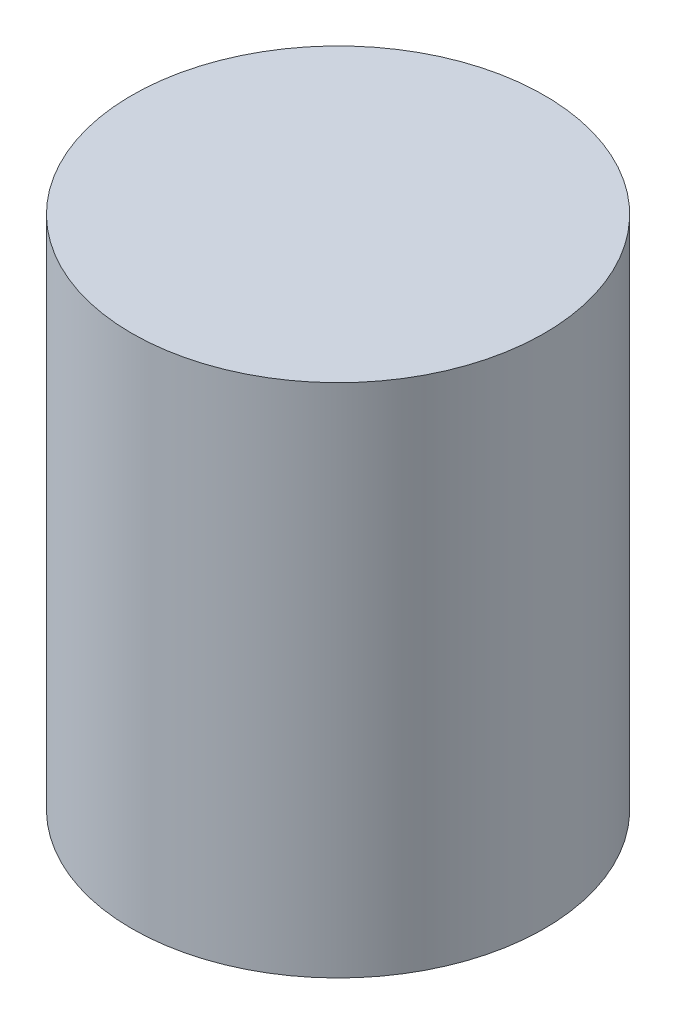
SolidWorks part; units mm, degrees
ref_plane "Front Plane" through (0, 0, 0) normal (0, 0, 1) x (1, 0, 0)
ref_plane "Top Plane" through (0, 0, 0) normal (0, 1, 0) x (1, 0, 0)
ref_plane "Right Plane" through (0, 0, 0) normal (1, 0, 0) x (0, 0, -1)
sketch "Sketch1" plane through (0, 0, 0) normal (0, 1, 0) x (1, 0, 0)
  circle A0 centre (0, 0) radius 40
  dimension "D1" = 80
extrude "Boss-Extrude1" add sketch "Sketch1" along normal blind 100
sketch "Sketch2" plane through (0, 0, 0) normal (0, -1, 0) x (1, 0, 0)
  circle A0 centre (0, 0) radius 10
  circle A1 centre (0, 22) radius 5
  circle A2 centre (0, -22) radius 5
  dimension "D2" = 10
  dimension "D3" = 20
  dimension "D4" = 10
  dimension "D1" = 22
  dimension "D5" = 22
extrude "Cut-Extrude1" cut sketch "Sketch2" against normal blind 20
